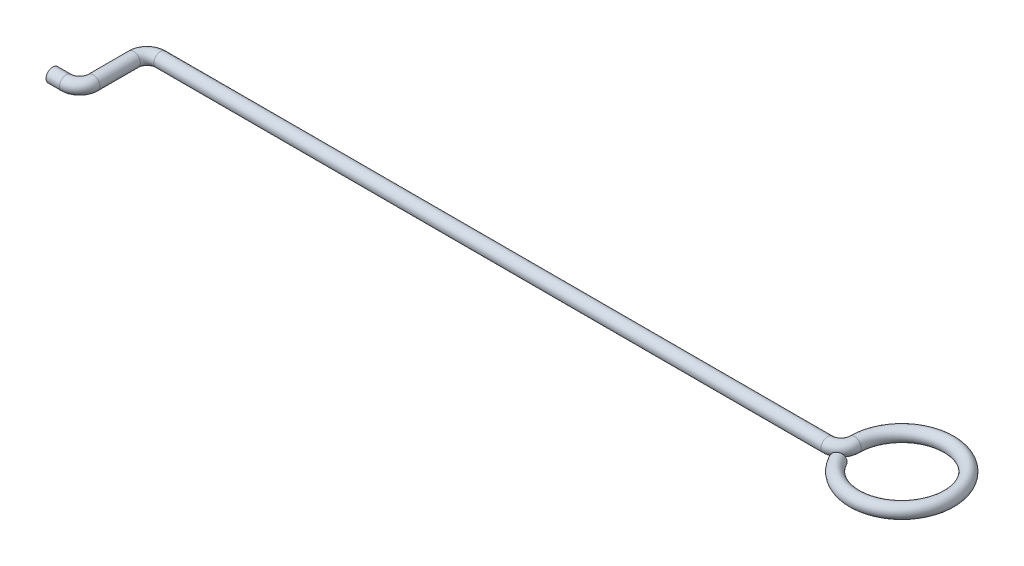
SolidWorks part; units mm, degrees
material "Stainless Steel (ferritic)"
ref_plane "Front" through (0, 0, 0) normal (0, 0, 1) x (1, 0, 0)
ref_plane "Top" through (0, 0, 0) normal (0, 1, 0) x (1, 0, 0)
ref_plane "Right" through (0, 0, 0) normal (1, 0, 0) x (0, 0, -1)
sketch "Sketch1" plane through (0, 0, 0) normal (0, 1, 0) x (1, 0, 0)
  line L0 (2, 1) -> (2, 4)
  line L1 (3, 5) -> (52.5, 5)
  line L4 (1, 0) -> (0, 0)
  arc A0 (2, 4) -> (3, 5) centre (3, 4) cw
  arc A1 (52.5, 5) -> (53.5, 6) centre (52.5, 6) ccw
  arc A3 (2, 1) -> (1, 0) centre (1, 1) cw
  arc A4 (53.5, 6) -> (53.9053, 4.3651) centre (57, 6) cw
  dimension "D2" = 1
  dimension "D1" = 3.5
  dimension "D3" = 3
  dimension "D4" = 1
  dimension "D5" = 55
sketch "Sketch2" plane through (0, 0, 0) normal (1, 0, 0) x (0, 0, -1)
  circle A0 centre (0, 0) radius 0.5
  dimension "D1" = 1
sweep "Sweep1" add profiles "Sketch2" path "Sketch1"
